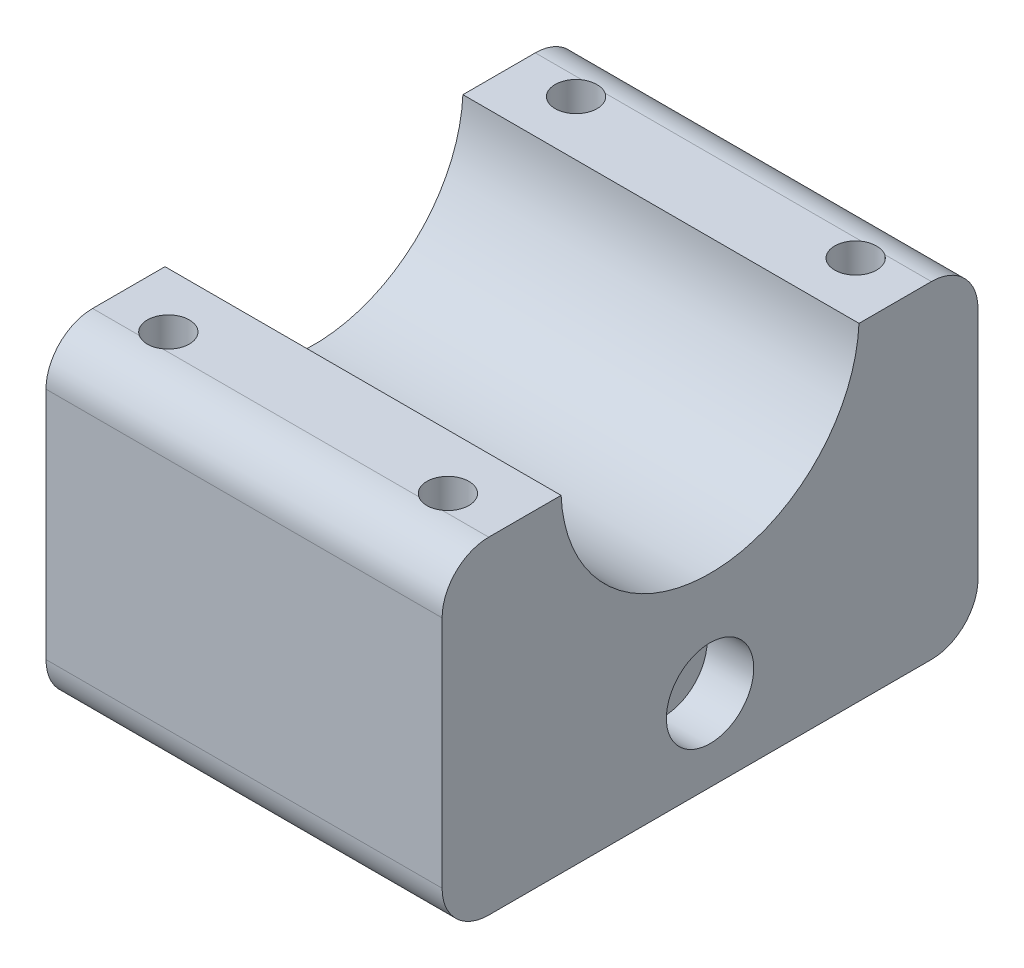
SolidWorks part; units mm, degrees
ref_plane "Front Plane" through (0, 0, 0) normal (0, 0, 1) x (1, 0, 0)
ref_plane "Top Plane" through (0, 0, 0) normal (0, 1, 0) x (1, 0, 0)
ref_plane "Right Plane" through (0, 0, 0) normal (1, 0, 0) x (0, 0, -1)
sketch "Sketch1" plane through (0, 0, 0) normal (1, 0, 0) x (0, 0, -1)
  line L0 (-19, -28.7) -> (19, -28.7)
  line L1 (23, -24.7) -> (23, -4.6)
  line L2 (19, -0.6) -> (-19, -0.6)
  line L3 (-23, -4.6) -> (-23, -24.7)
  arc A0 (19, -28.7) -> (23, -24.7) centre (19, -24.7) ccw
  arc A1 (23, -4.6) -> (19, -0.6) centre (19, -4.6) ccw
  arc A2 (-19, -0.6) -> (-23, -4.6) centre (-19, -4.6) ccw
  arc A3 (-23, -24.7) -> (-19, -28.7) centre (-19, -24.7) ccw
extrude "Boss-Extrude1" add sketch "Sketch1" along normal mid plane 34
sketch "Sketch2" plane through (0, 0, 0) normal (1, 0, 0) x (0, 0, -1)
  circle A0 centre (0, 0) radius 12.8
extrude "Cut-Extrude1" cut sketch "Sketch2" against normal through all and the other way through all
ref_plane "Plane1" through (0, -28.7, 0) normal (0, 1, 0) x (1, 0, 0)
sketch "Sketch3" plane through (0, -28.7, 0) normal (0, 1, 0) x (1, 0, 0)
  circle A0 centre (12, -17.5) radius 1.8
  circle A1 centre (12, 17.5) radius 1.8
  circle A2 centre (-12, -17.5) radius 1.8
  circle A3 centre (-12, 17.5) radius 1.8
extrude "Cut-Extrude2" cut sketch "Sketch3" along normal blind 28.5
ref_plane "Plane2" through (0, -28.7, 0) normal (0, 1, 0) x (1, 0, 0)
sketch "Sketch4" plane through (0, -28.7, 0) normal (0, 1, 0) x (1, 0, 0)
  circle A0 centre (12, -17.5) radius 3.25
  circle A1 centre (12, 17.5) radius 3.25
  circle A2 centre (-12, -17.5) radius 3.25
  circle A3 centre (-12, 17.5) radius 3.25
extrude "Cut-Extrude3" cut sketch "Sketch4" along normal blind 15.3
ref_plane "Plane3" through (0, -28.7, 0) normal (0, 1, 0) x (1, 0, 0)
sketch "Sketch5" plane through (0, -28.7, 0) normal (0, 1, 0) x (1, 0, 0)
  circle A0 centre (0, 0) radius 12.85
extrude "Cut-Extrude4" cut sketch "Sketch5" along normal blind 14
sketch "Sketch6" plane through (0, 0, 0) normal (1, 0, 0) x (0, 0, -1)
  circle A0 centre (0, -21.7) radius 1.8
extrude "Cut-Extrude5" cut sketch "Sketch6" against normal through all and the other way through all
ref_plane "Plane4" through (17, 0, 0) normal (1, 0, 0) x (0, 0, -1)
sketch "Sketch7" plane through (17, 0, 0) normal (1, 0, 0) x (0, 0, -1)
  circle A0 centre (0, -21.7) radius 3.75
extrude "Cut-Extrude6" cut sketch "Sketch7" against normal blind 4
ref_plane "Plane5" through (-17, 0, 0) normal (1, 0, 0) x (0, 0, -1)
sketch "Sketch8" plane through (-17, 0, 0) normal (1, 0, 0) x (0, 0, -1)
  line L0 (-2.85, -20.0546) -> (0, -18.4091)
  line L1 (0, -18.4091) -> (2.85, -20.0546)
  line L2 (2.85, -20.0546) -> (2.85, -23.3454)
  line L3 (2.85, -23.3454) -> (0, -24.9909)
  line L4 (0, -24.9909) -> (-2.85, -23.3454)
  line L5 (-2.85, -23.3454) -> (-2.85, -20.0546)
extrude "Cut-Extrude7" cut sketch "Sketch8" along normal blind 4.3
